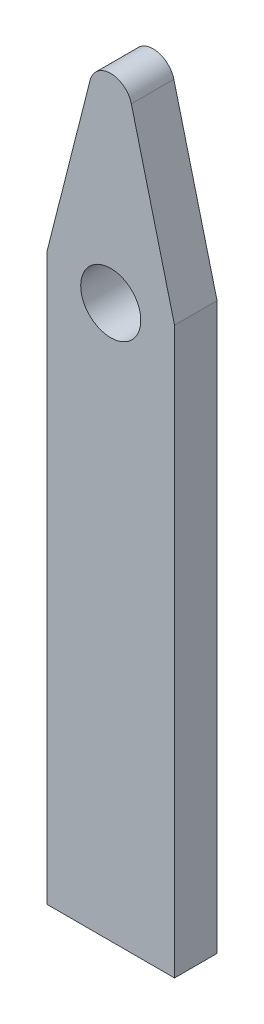
SolidWorks part; units mm, degrees
ref_plane "Front Plane" through (0, 0, 0) normal (0, 0, 1) x (1, 0, 0)
ref_plane "Top Plane" through (0, 0, 0) normal (0, 1, 0) x (1, 0, 0)
ref_plane "Right Plane" through (0, 0, 0) normal (1, 0, 0) x (0, 0, -1)
sketch "Sketch1" plane through (0, 0, 0) normal (0, 0, 1) x (1, 0, 0)
  line L0 (19.05, 51.687) -> (6.1548, 102.487)
  line L1 (-19.05, -117.223) -> (19.05, -117.223)
  line L2 (-19.05, -117.223) -> (-19.05, 51.687)
  line L4 (19.05, -117.223) -> (19.05, 51.687)
  line L5 (-6.1548, 102.487) -> (-19.05, 51.687)
  arc A0 (6.1548, 102.487) -> (-6.1548, 102.487) centre (0, 100.9247) ccw
  dimension "D1" = 6.35
  dimension "D2" = 168.91
  dimension "D3" = 38.1
  dimension "4.5" = 50.8
extrude "Boss-Extrude1" add sketch "Sketch1" along normal blind 12.7
sketch "Sketch4" plane through (0, 0, 0) normal (0, 0, -1) x (-1, 0, 0)
  line L0 (19.05, -117.223) -> (-19.05, -117.223) construction
  circle A0 centre (0, 47.877) radius 8.9767
  dimension "D1" = 165.1
extrude "Cut-Extrude1" cut sketch "Sketch4" against normal through all contours A0
